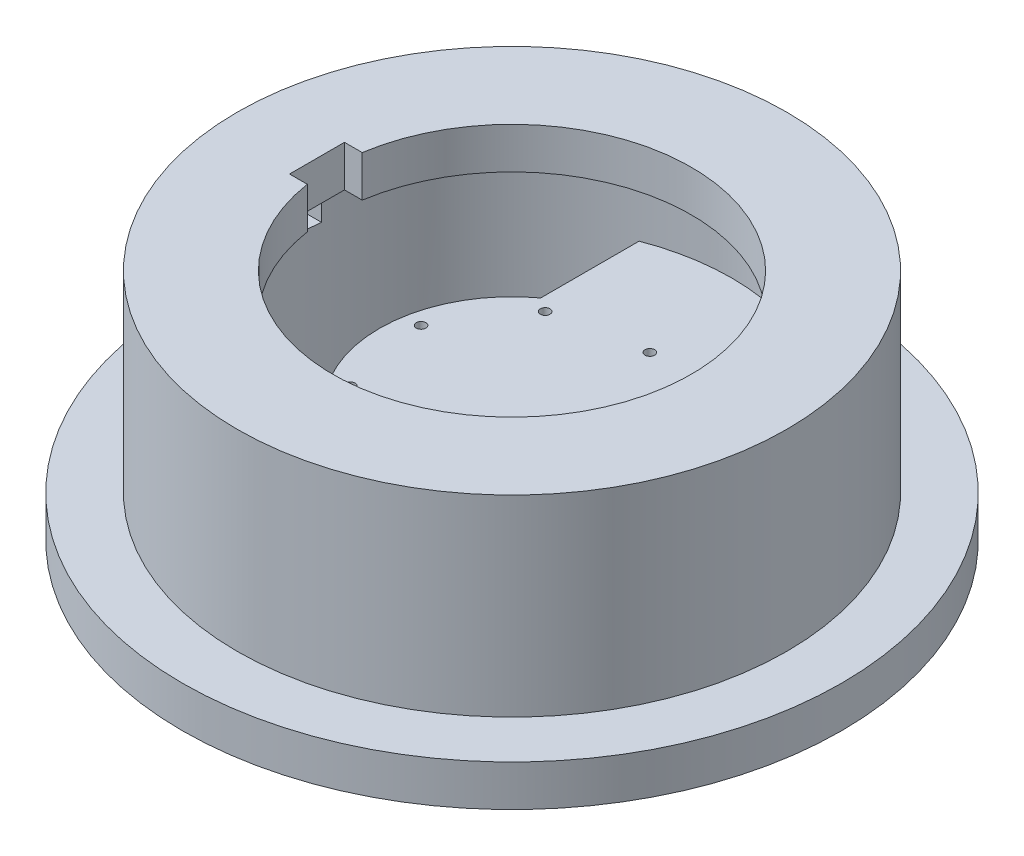
SolidWorks part; units mm, degrees
ref_plane "前视基准面" through (0, 0, 0) normal (0, 0, 1) x (1, 0, 0)
ref_plane "上视基准面" through (0, 0, 0) normal (0, 1, 0) x (1, 0, 0)
ref_plane "右视基准面" through (0, 0, 0) normal (1, 0, 0) x (0, 0, -1)
sketch "草图1" plane through (0, 0, 0) normal (0, 1, 0) x (1, 0, 0)
  circle A0 centre (0, 0) radius 120
extrude "凸台-拉伸1" add sketch "草图1" along normal blind 15
sketch "草图2" plane through (0, 15, 0) normal (0, 1, 0) x (1, 0, 0)
  circle A0 centre (0, 0) radius 100
extrude "凸台-拉伸2" add sketch "草图2" along normal blind 70
sketch "草图3" plane through (0, 0, 0) normal (0, -1, 0) x (1, 0, 0)
  circle A0 centre (0, 0) radius 80
extrude "切除-拉伸1" cut sketch "草图3" against normal blind 70
sketch "草图4" plane through (0, 85, 0) normal (0, 1, 0) x (1, 0, 0)
  circle A0 centre (0, 0) radius 48.25
extrude "切除-拉伸2" cut sketch "草图4" against normal blind 65
sketch "草图6" plane through (0, 0, 0) normal (0, 1, 0) x (1, 0, 0)
  circle A0 centre (0, 0) radius 48.25
extrude "凸台-拉伸3" add sketch "草图6" along normal blind 12.7 from offset 30 separate body
sketch "草图8" plane through (0, 0, 0) normal (0, 0, 1) x (1, 0, 0)
  line L0 (48.25, 42.7) -> (-48.25, 42.7) construction
  line L1 (-28.4924, 29.92) -> (29.3256, 29.92)
  line L2 (-28.4924, 29.92) -> (-28.4924, 42.7)
  line L3 (-28.4924, 42.7) -> (29.3256, 42.7)
  line L4 (29.3256, 29.92) -> (29.3256, 42.7)
  line L5 (-28.4924, 29.92) -> (29.3256, 42.7) construction
  line L6 (-28.4924, 42.7) -> (29.3256, 29.92) construction
  point P0 (0.4166, 36.31)
extrude "凸台-拉伸4" add sketch "草图8" along normal blind 85.7 and the other way blind 88.7
fillet "圆角1" radius 20 1 edges at (0.4467, 29.92, 79.9988)
fillet "圆角2" radius 20 1 edges at (0.4467, 29.92, -79.9988)
sketch "草图10" plane through (0, 85, 0) normal (0, 1, 0) x (1, 0, 0)
  line L1 (-70.9668, -10) -> (-47.0332, -10)
  line L2 (-70.9668, -10) -> (-70.9668, 10)
  line L3 (-70.9668, 10) -> (-47.0332, 10)
  line L4 (-47.0332, -10) -> (-47.0332, 10)
  line L5 (-70.9668, -10) -> (-47.0332, 10) construction
  line L6 (-70.9668, 10) -> (-47.0332, -10) construction
  point P0 (-59, 0)
extrude "切除-拉伸3" cut sketch "草图10" against normal blind 25
sketch "草图11" plane through (0, 85, 0) normal (0, 1, 0) x (1, 0, 0)
  circle A0 centre (0, 0) radius 65.2781
extrude "切除-拉伸4" cut sketch "草图11" against normal blind 19
sketch "草图12" plane through (29.3256, 0, 0) normal (1, 0, 0) x (0, 0, -1)
  line L1 (-10, 70) -> (10, 70)
  line L2 (-10, 70) -> (-10, 55.5871)
  line L3 (-10, 55.5871) -> (10, 55.5871)
  line L4 (10, 70) -> (10, 55.5871)
extrude "切除-拉伸5" cut sketch "草图12" against normal blind 165
sketch "草图13" plane through (0, 29.92, 0) normal (0, -1, 0) x (1, 0, 0)
  circle A0 centre (-8.5329, 41.6346) radius 1.75
  circle A1 centre (23.4064, 35.4738) radius 1.75
  circle A2 centre (41.6346, 8.5329) radius 1.75
  circle A3 centre (35.4738, -23.4064) radius 1.75
  circle A4 centre (8.5329, -41.6346) radius 1.75
  circle A5 centre (-23.4064, -35.4738) radius 1.75
  circle A6 centre (-41.6346, -8.5329) radius 1.75
  circle A7 centre (-35.4738, 23.4064) radius 1.75
  point P19 (0, 0)
  dimension "D1" = 42.5
  dimension "D2" = 8
extrude "切除-拉伸6" cut sketch "草图13" against normal blind 25
